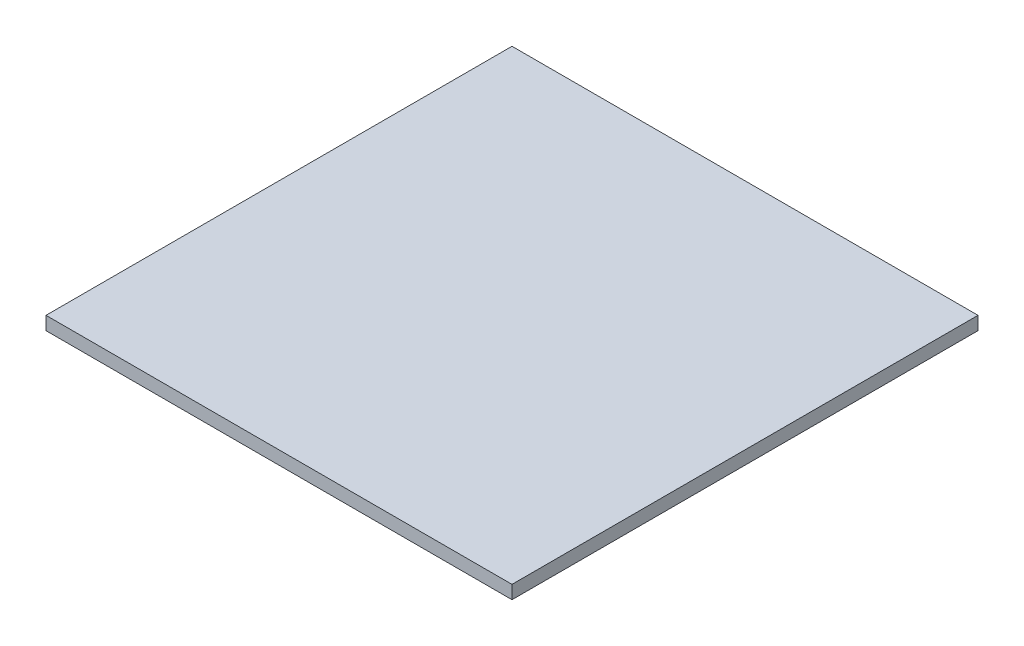
SolidWorks part; units mm, degrees
material "Szkło"
ref_plane "Płaszczyzna przednia" through (0, 0, 0) normal (0, 0, 1) x (1, 0, 0)
ref_plane "Płaszczyzna górna" through (0, 0, 0) normal (0, 1, 0) x (1, 0, 0)
ref_plane "Płaszczyzna prawa" through (0, 0, 0) normal (1, 0, 0) x (0, 0, -1)
sketch "Szkic1" plane through (0, 0, 0) normal (0, 1, 0) x (1, 0, 0)
  line L1 (-143.0061, -53.0368) -> (136.9939, -53.0368)
  line L2 (-143.0061, -53.0368) -> (-143.0061, 226.9632)
  line L3 (-143.0061, 226.9632) -> (136.9939, 226.9632)
  line L4 (136.9939, -53.0368) -> (136.9939, 226.9632)
  dimension "D1" = 280
extrude "Dodanie-wyciągnięcie1" add sketch "Szkic1" along normal blind 8
